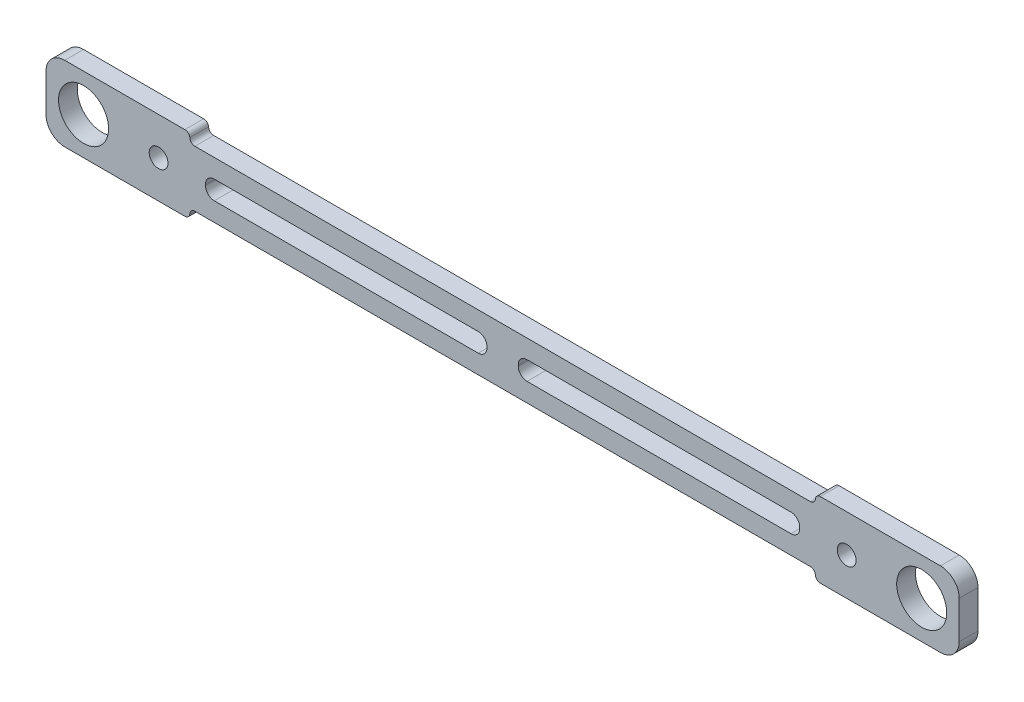
SolidWorks part; units mm, degrees
material "Maple"
ref_plane "Front Plane" through (0, 0, 0) normal (0, 0, 1) x (1, 0, 0)
ref_plane "Top Plane" through (0, 0, 0) normal (0, 1, 0) x (1, 0, 0)
ref_plane "Right Plane" through (0, 0, 0) normal (1, 0, 0) x (0, 0, -1)
sketch "Sketch1" plane through (0, 0, 0) normal (0, 0, 1) x (1, 0, 0)
  line L0 (0, 0) -> (25, 0) construction
  line L1 (-49.2, 4.5) -> (49.2, 4.5)
  line L2 (50, 5.3) -> (50, 5.2)
  line L3 (50.8, 6) -> (70, 6)
  line L4 (73, 3) -> (73, -3)
  line L5 (70, -6) -> (50.8, -6)
  line L6 (50, -5.2) -> (50, -5.3)
  line L7 (49.2, -4.5) -> (-49.2, -4.5)
  line L8 (-50, -5.3) -> (-50, -5.2)
  line L9 (-50.8, -6) -> (-70, -6)
  line L10 (-73, -3) -> (-73, 3)
  line L11 (-70, 6) -> (-50.8, 6)
  line L12 (-50, 5.2) -> (-50, 5.3)
  line L13 (-73, -6) -> (73, 6) construction
  line L14 (-73, 6) -> (73, -6) construction
  line L15 (0, 0) -> (-25, 0) construction
  line L17 (-46.1, 1.5) -> (-3.9, 1.5)
  line L18 (-47.5, 0.1) -> (-47.5, -0.1)
  line L19 (-46.1, -1.5) -> (-3.9, -1.5)
  line L20 (-2.5, 0.1) -> (-2.5, -0.1)
  line L21 (-47.5, 1.5) -> (-2.5, -1.5) construction
  line L22 (-47.5, -1.5) -> (-2.5, 1.5) construction
  line L23 (46.1, 1.5) -> (3.9, 1.5)
  line L24 (47.5, 0.1) -> (47.5, -0.1)
  line L25 (46.1, -1.5) -> (3.9, -1.5)
  line L26 (2.5, 0.1) -> (2.5, -0.1)
  line L27 (47.5, 1.5) -> (2.5, -1.5) construction
  line L28 (47.5, -1.5) -> (2.5, 1.5) construction
  circle A0 centre (-55, 0) radius 1.5
  circle A1 centre (-67, 0) radius 4
  circle A2 centre (67, 0) radius 4
  circle A3 centre (55, 0) radius 1.5
  arc A4 (73, -3) -> (70, -6) centre (70, -3) cw
  arc A5 (73, 3) -> (70, 6) centre (70, 3) ccw
  arc A6 (-70, -6) -> (-73, -3) centre (-70, -3) cw
  arc A7 (-70, 6) -> (-73, 3) centre (-70, 3) ccw
  arc A8 (50.8, -6) -> (50, -5.2) centre (50.8, -5.2) cw
  arc A9 (50, -5.3) -> (49.2, -4.5) centre (49.2, -5.3) ccw
  arc A10 (50, 5.3) -> (49.2, 4.5) centre (49.2, 5.3) cw
  arc A11 (50.8, 6) -> (50, 5.2) centre (50.8, 5.2) ccw
  arc A12 (-49.2, 4.5) -> (-50, 5.3) centre (-49.2, 5.3) cw
  arc A13 (-50, 5.2) -> (-50.8, 6) centre (-50.8, 5.2) ccw
  arc A14 (-50, -5.3) -> (-49.2, -4.5) centre (-49.2, -5.3) cw
  arc A15 (-50, -5.2) -> (-50.8, -6) centre (-50.8, -5.2) cw
  arc A16 (47.5, -0.1) -> (46.1, -1.5) centre (46.1, -0.1) cw
  arc A17 (47.5, 0.1) -> (46.1, 1.5) centre (46.1, 0.1) ccw
  arc A18 (3.9, -1.5) -> (2.5, -0.1) centre (3.9, -0.1) cw
  arc A19 (3.9, 1.5) -> (2.5, 0.1) centre (3.9, 0.1) ccw
  arc A20 (-2.5, 0.1) -> (-3.9, 1.5) centre (-3.9, 0.1) ccw
  arc A21 (-2.5, -0.1) -> (-3.9, -1.5) centre (-3.9, -0.1) cw
  arc A22 (-46.1, -1.5) -> (-47.5, -0.1) centre (-46.1, -0.1) cw
  arc A23 (-46.1, 1.5) -> (-47.5, 0.1) centre (-46.1, 0.1) ccw
  point P4 (0, 0)
  point P13 (0, 0)
  point P34 (0, 0)
  point P35 (0, 0)
  point P36 (0, 0)
  point P55 (50, 4.5)
  point P60 (-50, 4.5)
  dimension "D10" = 3
  dimension "D11" = 8
  dimension "D15" = 3
  dimension "D16" = 0.8
  dimension "D17" = 1.4
  dimension "D1" = 100
  dimension "D2" = 12
  dimension "D3" = 9
  dimension "D4" = 146
  dimension "D5" = 25
  dimension "D6" = 25
  dimension "D7" = 6
  dimension "D8" = 3
  dimension "D9" = 45
  dimension "D12" = 6
  dimension "D13" = 18
  dimension "D14" = 110
extrude "Boss-Extrude1" add sketch "Sketch1" along normal blind 3
